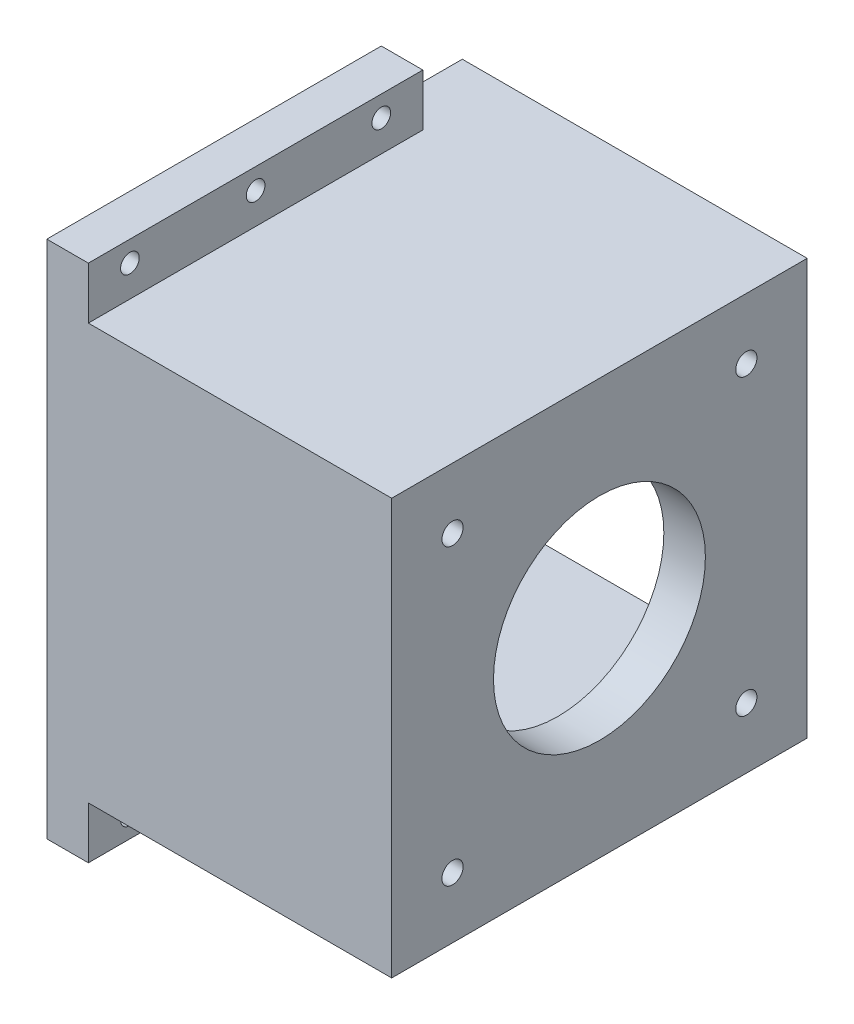
SolidWorks part; units mm, degrees
ref_plane "前视基准面" through (0, 0, 0) normal (0, 0, 1) x (1, 0, 0)
ref_plane "上视基准面" through (0, 0, 0) normal (0, 1, 0) x (1, 0, 0)
ref_plane "右视基准面" through (0, 0, 0) normal (1, 0, 0) x (0, 0, -1)
other "Configuration Table"
sketch "草图1" plane through (0, 0, 0) normal (0, 0, 1) x (1, 0, 0)
  line L0 (20, 225) -> (20, 250)
  line L1 (0, 0) -> (20, 0)
  line L2 (0, 0) -> (0, 250)
  line L3 (0, 250) -> (20, 250)
  line L4 (20, 0) -> (20, 25)
  line L5 (20, 25) -> (166, 25)
  line L7 (20, 225) -> (166, 225)
  line L8 (166, 25) -> (166, 225)
  point P9 (10, 0)
  dimension "D1" = 20
  dimension "D2" = 166
  dimension "D3" = 250
  dimension "D4" = 200
  dimension "D5" = 25
extrude "凸台-拉伸1" add sketch "草图1" against normal blind 200
sketch "草图2" plane through (0, 0, 0) normal (-1, 0, 0) x (0, 0, 1)
  line L0 (-200, 250) -> (-161, 250)
  line L1 (-200, 250) -> (0, 250) construction
  line L2 (-161, 250) -> (-161, 225)
  line L3 (-200, 0) -> (0, 0) construction
  line L4 (-161, 0) -> (-200, 0)
  line L5 (-200, 0) -> (-200, 25)
  line L6 (-161, 25) -> (-161, 0)
  line L11 (-200, 225) -> (-161, 225)
  line L13 (-200, 25) -> (-161, 25)
  line L15 (-200, 225) -> (-200, 250)
  dimension "D1" = 39
  dimension "D2" = 200
extrude "切除-拉伸1" cut sketch "草图2" against normal blind 20
sketch "草图3" plane through (0, 0, -200) normal (0, 0, -1) x (-1, 0, 0)
  line L0 (-166, 25) -> (-166, 225) construction
  line L1 (-146, 202.5833) -> (-20, 202.5833)
  line L2 (-146, 202.5833) -> (-146, 42.5833)
  line L3 (-146, 42.5833) -> (-20, 42.5833)
  line L4 (-20, 202.5833) -> (-20, 42.5833)
  dimension "D1" = 160
  dimension "D2" = 126
  dimension "D3" = 20
extrude "切除-拉伸2" cut sketch "草图3" against normal blind 180
sketch "草图4" plane through (166, 0, 0) normal (1, 0, 0) x (0, 0, -1)
  circle A0 centre (100, 125) radius 51
  point P8 (100, 125)
  dimension "D1" = 102
extrude "切除-拉伸3" cut sketch "草图4" against normal up to next
sketch "草图5" plane through (20, 0, 0) normal (1, 0, 0) x (0, 0, -1)
  circle A0 centre (100, 125) radius 25.5
  dimension "D1" = 51
extrude "切除-拉伸4" cut sketch "草图5" against normal blind 15
sketch "草图6" plane through (0, 0, 0) normal (-1, 0, 0) x (0, 0, 1)
  circle A0 centre (-100, 125) radius 57.15
  point P5 (-100, 125)
  dimension "D1" = 114.3
extrude "切除-拉伸5" cut sketch "草图6" against normal blind 5
sketch "草图7" plane through (20, 0, 0) normal (1, 0, 0) x (0, 0, -1)
  line L0 (0, 125) -> (325.7801, 125) construction
  line L1 (0, 25) -> (0, 225) construction
  circle A0 centre (20, 240) radius 4.5
  circle A1 centre (80.5, 240) radius 4.5
  circle A2 centre (141, 240) radius 4.5
  circle A3 centre (141, 10) radius 4.5
  circle A4 centre (80.5, 10) radius 4.5
  circle A5 centre (20, 10) radius 4.5
  point P7 (20, 240)
  dimension "D1" = 9
  dimension "D2" = 3
extrude "切除-拉伸6" cut sketch "草图7" against normal up to next
sketch "草图8" plane through (166, 0, 0) normal (1, 0, 0) x (0, 0, -1)
  circle A0 centre (100, 125) radius 100 construction
  point P14 (170.71, 195.7114)
  dimension "D1" = 200
hole_wizard "M12 螺纹孔1" positions "草图8" profile "草图9" tap size "M12" standard "GB"
sketch "草图9" plane through (166, 195.7114, -170.71) normal (0, 1, 0) x (0, 0, -1)
  line L0 (0, 0) -> (0, 29.25)
  line L1 (0, 29.25) -> (5.1, 26.1856)
  line L2 (5.1, 26.1856) -> (5.1, 0)
  line L5 (5.1, 0) -> (0, 0)
  line L10 (0, 29.25) -> (-5.1, 26.1856) construction
  line L11 (0, -6.35) -> (0, 107.95) construction
  dimension "螺纹孔钻头直径" = 10.2
  dimension "螺纹孔钻头深度" = 29.25
  dimension "导头角度" = 118
cosmetic thread "孔螺纹线1" parameters "D1"=24, "D2"=12
pattern_circular "阵列(圆周)1" count 4 every 90 about axis through (0, 125, -100) along (1, 0, 0) of "M12 螺纹孔1"
